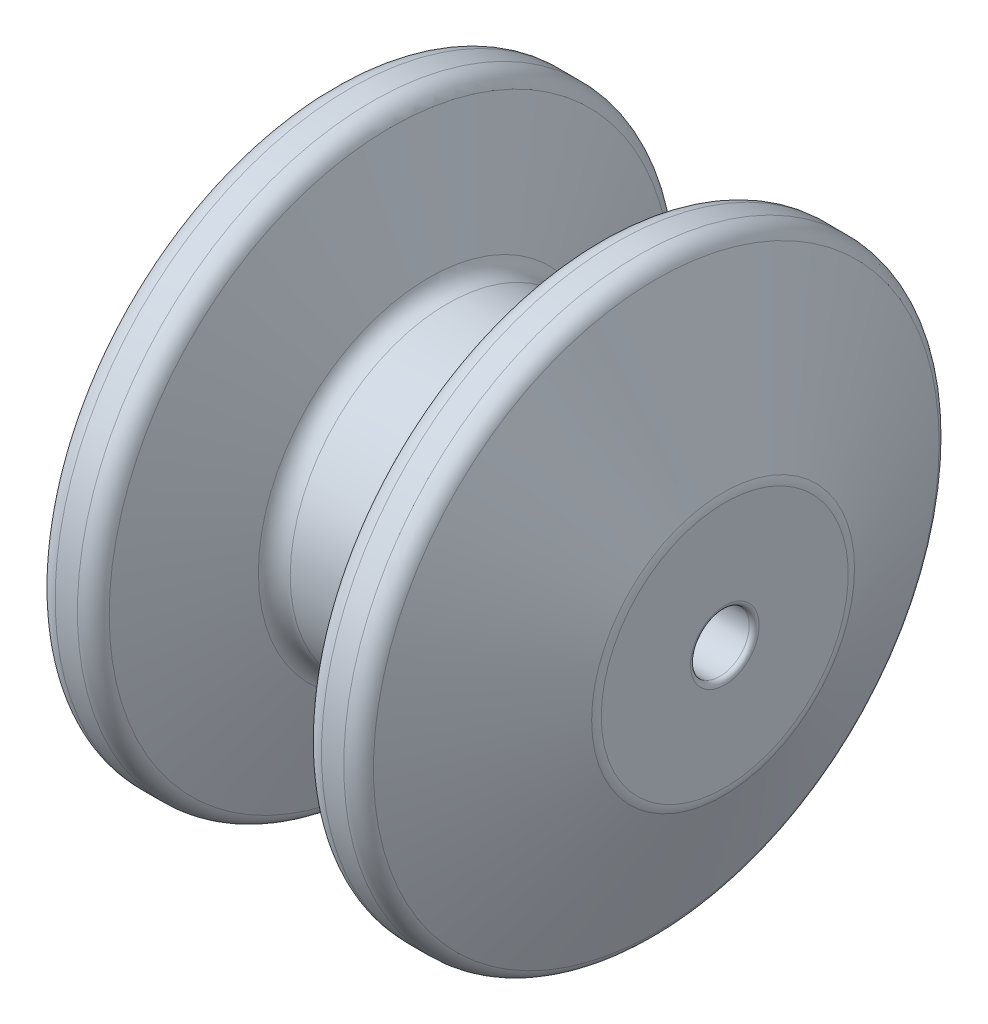
SolidWorks part; units mm, degrees
ref_plane "Alzado" through (0, 0, 0) normal (0, 0, 1) x (1, 0, 0)
ref_plane "Planta" through (0, 0, 0) normal (0, 1, 0) x (1, 0, 0)
ref_plane "Vista lateral" through (0, 0, 0) normal (1, 0, 0) x (0, 0, -1)
sketch "Croquis1" plane through (0, 0, 0) normal (0, 0, 1) x (1, 0, 0)
  line L0 (-29.0316, 0) -> (29.0316, 0) construction
  line L1 (-6.1794, 16) -> (6.1794, 16) construction
  line L2 (-23.5, 3) -> (23.5, 3) construction
  line L4 (-16, 30) -> (-11, 30)
  line L5 (-11, 30) -> (-6.1794, 16)
  line L6 (6.1794, 16) -> (11, 30) construction
  line L7 (11, 30) -> (16, 30) construction
  line L9 (0, 0) -> (0, 30) construction
  line L10 (-6.1794, 16) -> (0, 16)
  line L11 (0, 16) -> (0, 3) construction
  line L13 (-23.5, 3) -> (-23.5, 13)
  line L14 (-23.5, 13) -> (-16, 30)
  line L15 (23.5, 3) -> (23.5, 13)
  line L16 (23.5, 13) -> (16, 30)
  line L17 (16, 30) -> (11, 30)
  line L18 (11, 30) -> (6.1794, 16)
  line L19 (-23.5, 3) -> (23.5, 3)
  line L20 (6.1794, 16) -> (0, 16)
  point P0 (0, 16)
  point P4 (0, 0)
  point P6 (0, 3)
  point P8 (0, 0)
  point P18 (-13.5, 30)
  point P19 (13.5, 30)
  dimension "D1" = 14
  dimension "D2" = 22
  dimension "D3" = 5
  dimension "D4" = 3
  dimension "D5" = 60
  dimension "D6" = 38
  dimension "D7" = 47
  dimension "D8" = 10
revolve "Revolución1" add sketch "Croquis1" angle 360 about L0
fillet "Redondeo2" radius 2 8 edges at (-16, 0, 30) (-23.5, 0, 13) (23.5, 0, 13) (16, 0, 30) (11, 0, 30) (6.1794, 0, 16) (-6.1794, 0, 16) (-11, 0, 30)
fillet "Redondeo3" radius 0.5 2 edges at (23.5, 0, 3) (-23.5, 0, 3)
sketch "Croquis2" plane through (0, 0, 0) normal (0, 0, 1) x (1, 0, 0)
  line L0 (-6.6439, 17.3489) -> (-10.5355, 28.6511) construction
ref_plane "Plano1" through (-0.5991, -0.2063, 0) normal (0.9455, 0.3256, 0) x (-0.3256, 0.9455, 0)
ref_plane "Plano2" through (0, 5, 0) normal (0, 1, 0) x (1, 0, 0)
surface "Superficie-Equidistancia1" parameters "D1"=0.2
mirror "Simetría2" about plane through (0, 0, 0) normal (1, 0, 0) of bodies 101 167
